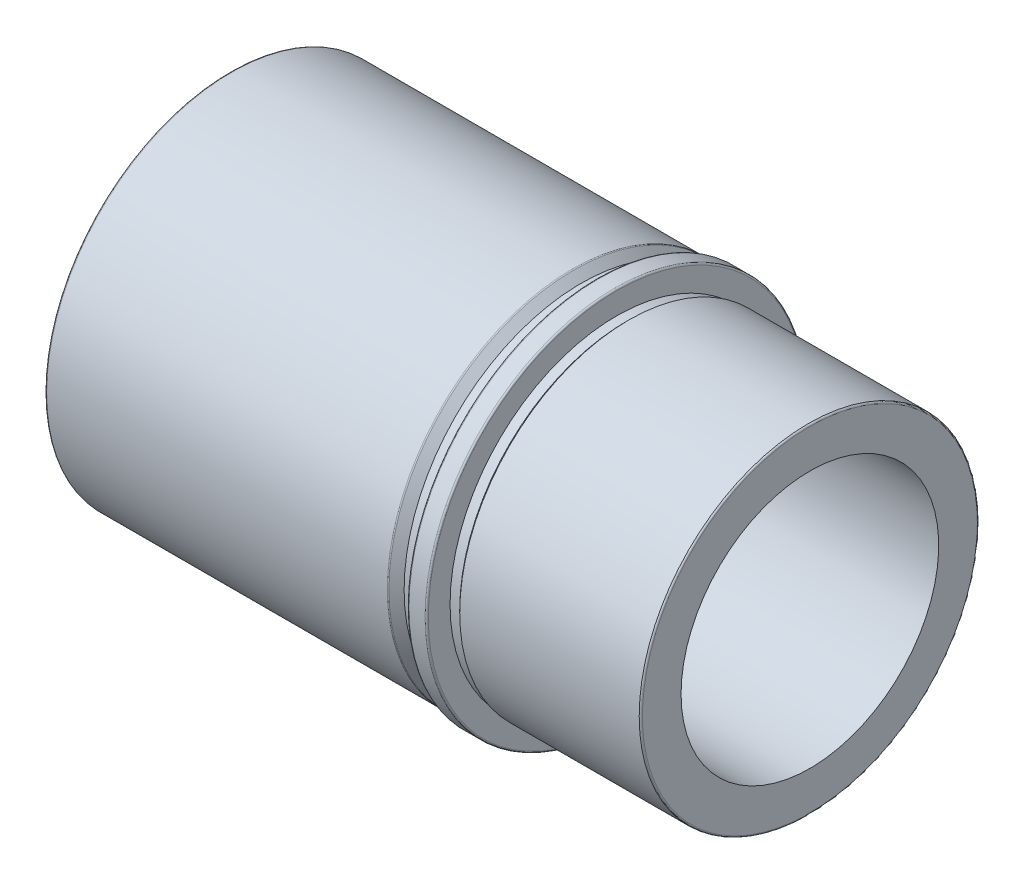
SolidWorks part; units mm, degrees
ref_plane "Front" through (0, 0, 0) normal (0, 0, 1) x (1, 0, 0)
ref_plane "Top" through (0, 0, 0) normal (0, 1, 0) x (1, 0, 0)
ref_plane "Right" through (0, 0, 0) normal (1, 0, 0) x (0, 0, -1)
sketch "Sketch1" plane through (0, 0, 0) normal (0, 0, 1) x (1, 0, 0)
  line L0 (-138.7582, 0) -> (33.4427, 0) construction
  line L1 (-114, -57.5) -> (-7.5, -57.5)
  line L2 (-7.5, -57.5) -> (-5, -55)
  line L3 (-5, -55) -> (0, -55)
  line L4 (0, -55) -> (0, -59)
  line L5 (0, -59) -> (6, -59)
  line L6 (6, -59) -> (6, -51.7334)
  line L7 (6, -51.7334) -> (9, -51.7334)
  line L8 (9, -51.7334) -> (9.7666, -52.5)
  line L9 (9.7666, -52.5) -> (66, -52.5)
  line L10 (66, -52.5) -> (66, -40)
  line L12 (-114, -40) -> (66, -40)
  line L13 (-114, -40) -> (-114, -57.5)
  dimension "D2" = 115
  dimension "D3" = 6
  dimension "D4" = 105
  dimension "D5" = 118
  dimension "D6" = 80
  dimension "D7" = 60
  dimension "D8" = 4
  dimension "D9" = 5
  dimension "D10" = 135
  dimension "D11" = 3
  dimension "D12" = 135
  dimension "D13" = 180
revolve "Base-Revolve" add sketch "Sketch1" angle 360 about L0
fillet "Fillet1" radius 0.5 6 edges at (6, 0, 59) (0, 0, 59) (-7.5, 0, 57.5) (-114, 0, 57.5) (-114, 0, 40) (66, 0, 52.5)
